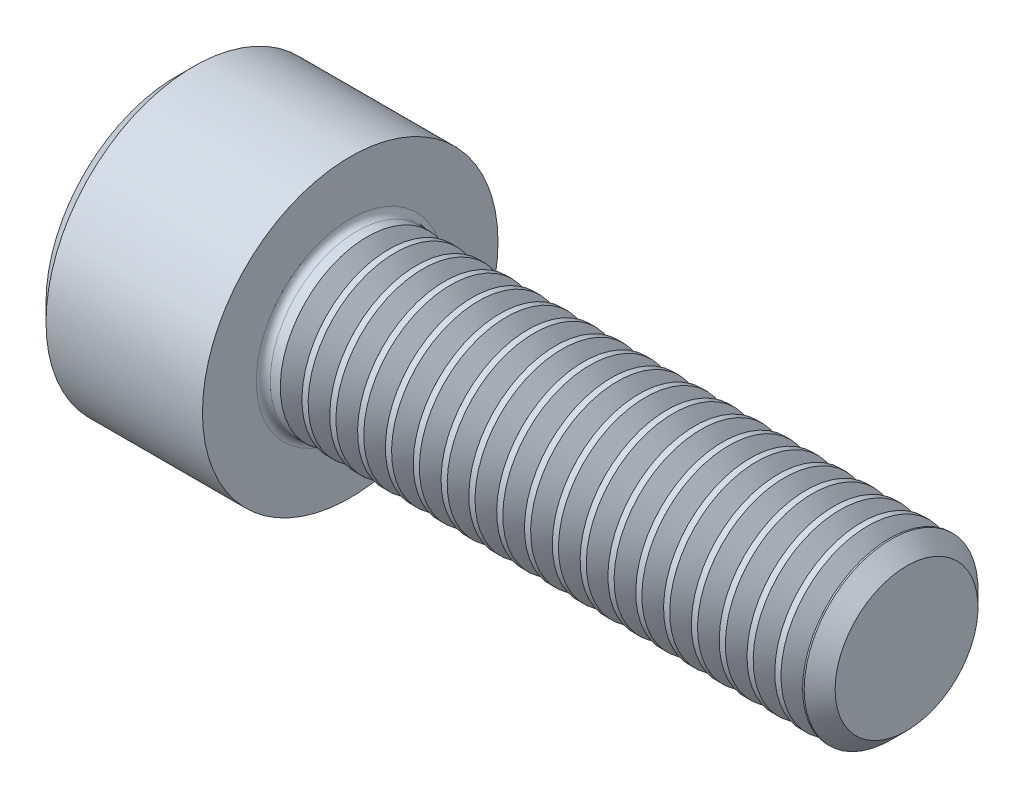
SolidWorks part; units mm, degrees
revolve "Base-Revolve" add sketch "BodySke"
sketch "BodySke" plane through (0, 0, 0) normal (0, 0, 1) x (1, 0, 0)
  line L0 (0, 0) -> (0, 3.75)
  line L1 (0.5, 4.25) -> (5, 4.25)
  line L2 (5, 4.25) -> (5, 2.5)
  line L3 (5, 2.5) -> (20.555, 2.5)
  line L4 (21, 2.055) -> (21, 0)
  line L5 (21, 0) -> (0, 0)
  line L6 (-31.75, 0) -> (127, 0) construction
  line L7 (0, 3.75) -> (0.5, 4.25)
  line L8 (21, 2.055) -> (20.555, 2.5)
  line L9 (0, -3.75) -> (0.5, -4.25) construction
  line L10 (21, -2.055) -> (20.555, -2.5) construction
  line L11 (5.8, 9.525) -> (5.8, 3.175) construction
  line L12 (5, 9.525) -> (5, 3.175) construction
  line L13 (-29, 9.525) -> (-29, 3.175) construction
  dimension "Diameter" = 5
  dimension "Head_ht" = 5
  dimension "Length" = 16
  dimension "Body_ch_ang" = 45
  dimension "Head_dia" = 8.5
  dimension "Head_ch_ang" = 45
  dimension "Minor_dia" = 4.11
  dimension "Advance" = 0.8
  dimension "Thread_nom" = 16
  dimension "Thread_length" = 50
  dimension "Head_ch_ht" = 0.5
cosmetic thread "ThreadCosmetic" [suppressed]
fillet "Fillet1" radius 0.2 1 edges at (5, 0, 2.5)
ref_plane "Plane1" through (0, 0, 0) normal (0, 0, 1) x (1, 0, 0)
ref_plane "Plane2" through (0, 0, 0) normal (0, 1, 0) x (1, 0, 0)
ref_plane "Plane3" through (0, 0, 0) normal (1, 0, 0) x (0, 0, -1)
sketch "Sketch2" plane through (0, 0, 0) normal (0, 0, 1) x (1, 0, 0)
  line L0 (0, 2.042) -> (2.5, 2.042)
  line L1 (2.5, 2.042) -> (3.6789, 0)
  line L2 (-31.75, 0) -> (127, 0) construction
  line L3 (3.6789, 0) -> (0, 0)
  line L4 (0, 0) -> (0, 2.042)
  line L5 (0, 3.75) -> (0, -3.75) construction
  line L6 (0, 0) -> (47.625, 0) construction
  line L7 (5, -4.25) -> (5, 4.25) construction
  dimension "D1" = 2.042
  dimension "D2" = 60
revolve "Hex-PreBroach" cut sketch "Sketch2" angle 360 about L6
sketch "Sketch3" plane through (0, 0, 0) normal (-1, 0, 0) x (0, 0.5, 0.866)
  line L0 (1.1789, 2.042) -> (-1.1789, 2.042)
  line L1 (-1.1789, 2.042) -> (-2.3579, 0)
  line L2 (1.1789, 2.042) -> (2.3579, 0)
  line L3 (1.1789, -2.042) -> (2.3579, 0)
  line L4 (1.1789, -2.042) -> (-1.1789, -2.042)
  line L5 (-1.1789, -2.042) -> (-2.3579, 0)
  dimension "D1" = 2.042
  dimension "D2" = 2.042
  dimension "Hex_size" = 4.084
extrude "Hex" cut sketch "Sketch3" against normal blind 2.5
sketch "Sketch4" plane through (0, 0, 0) normal (-1, 0, 0) x (0, 0, 1)
  line L0 (0, 0) -> (2.3876, 0)
  line L1 (0, 0) -> (6.1484, 3.5498) construction
  line L2 (0, 0) -> (1.1938, 2.0677)
  line L3 (1.9883, 0.576) -> (2.2704, 0.7389)
  line L4 (1.493, 1.4339) -> (1.7751, 1.5968)
  arc A0 (1.9883, 0.576) -> (1.493, 1.4339) centre (0, 0) ccw
  arc A1 (2.3876, 0) -> (2.2704, 0.7389) centre (0, 0) ccw
  arc A2 (1.1938, 2.0677) -> (1.7751, 1.5968) centre (0, 0) cw
  dimension "D1" = 30
  dimension "D2" = 60
  dimension "Spline_p_dim" = 0.9906
  dimension "D3" = 0.4953
extrude "Spline" [suppressed] cut sketch "Sketch4" against normal blind 2.5
pattern_circular "CirPattern1" [suppressed] count 6 every 60
sketch "Sketch5" plane through (0, 0, 0) normal (0, 0, 1) x (1, 0, 0)
  line L0 (-31.75, 0) -> (127, 0) construction
  line L2 (0, 3.75) -> (0, -3.75) construction
  circle A0 centre (2, 0) radius 0.675
  dimension "Drilled_hole_dia" = 1.35
  dimension "Drilled_hole_loc" = 2
extrude "Hole" [suppressed] cut sketch "Sketch5" against normal through all and the other way through all
pattern_circular "Drilled-4" [suppressed] count 2 every 60
pattern_circular "Drilled-6" [suppressed] count 3 every 60
sketch "ThdSchSke" plane through (0, 0, 0) normal (0, 0, 1) x (1, 0, 0)
  line L0 (5.8, -2.055) -> (5.4884, -2.5)
  line L1 (5.8, -2.055) -> (6.1116, -2.5)
  line L2 (6.1116, -2.5) -> (6.1116, -3.125)
  line L3 (-3.175, 0) -> (5.1513, 0) construction
  line L5 (6.1116, -3.125) -> (5.4884, -3.125)
  line L6 (5.4884, -3.125) -> (5.4884, -2.5)
  line L7 (0, 3.75) -> (0, -3.75) construction
  dimension "Thread_minor" = 4.11
  dimension "Diameter" = 5
  dimension "Start" = 5.8
revolve "ThreadSchematic" cut sketch "ThdSchSke" angle 360 about L3
pattern_linear "ThdSchPat" count 19 spacing 0.8 along (1, 0, 0) of "ThreadSchematic"
equation "\"D2@Sketch3\" = \"Hex_size@Sketch3\" / 2"
equation "\"D1@Sketch3\" = \"Hex_size@Sketch3\" / 2"
equation "\"D1@Sketch2\" = \"Hex_size@Sketch3\" / 2"
equation "\"D3@Sketch4\" = \"Spline_p_dim@Sketch4\" / 2"
equation "\"Thread_minor@ThreadCosmetic\"  =  \"Minor_dia@BodySke\""
equation "\"D2@CirPattern1\" = 360 / \"Num_teeth@CirPattern1\""
equation "\"Wall_thickness@Sketch2\" = \"Head_ht@BodySke\" - \"Key_eng@Hex\""
equation "\"Thread_length@ThreadCosmetic\" = ((sgn( (\"Length@BodySke\" - \"Advance@BodySke\" ) - \"Thread_nom@BodySke\" )-1)*( (\"Length@BodySke\" - \"Advance@BodySke\" ) - \"Thread_nom@BodySke\" ))/-2+ \"Thread_nom@BodySke\""
equation "\"Thread_minor@ThdSchSke\" = \"Minor_dia@BodySke\""
equation "\"Diameter@ThdSchSke\" = \"Diameter@BodySke\""
equation "\"Overcut@ThdSchSke\" = \"Diameter@BodySke\" * 1.25"
equation "\"Start@ThdSchSke\" = \"Head_ht@BodySke\" + \"Length@BodySke\" - \"Thread_length@ThreadCosmetic\"  '---Non-countersunk---"
equation "\"Num_threads@ThdSchPat\" = int( \"Thread_length@ThreadCosmetic\" / \"Advance@BodySke\" + 0.999 )  + 1"
equation "\"Advance@ThdSchPat\" = \"Thread_length@ThreadCosmetic\" /  (\"Num_threads@ThdSchPat\" - 1) 'relax it"
equation "\"Num_threads@ThdSchPat\" = \"Num_threads@ThdSchPat\" - sgn( \"Num_threads@ThdSchPat\" - 1) '---chamfered tips only---"
